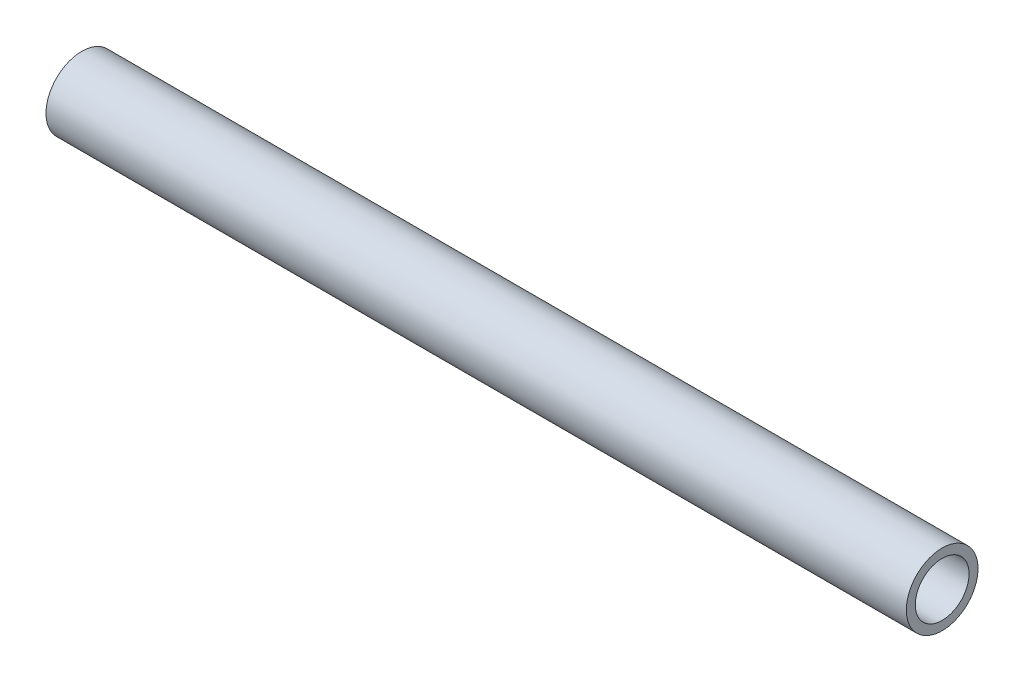
SolidWorks part; units mm, degrees
ref_plane "Front Plane" through (0, 0, 0) normal (0, 0, 1) x (1, 0, 0)
ref_plane "Top Plane" through (0, 0, 0) normal (0, 1, 0) x (1, 0, 0)
ref_plane "Right Plane" through (0, 0, 0) normal (1, 0, 0) x (0, 0, -1)
sketch "Sketch1" plane through (0, 0, 0) normal (0, 0, 1) x (1, 0, 0)
  line L0 (-50.4967, 0) -> (-145.3956, 0) construction
  line L2 (0, 4.7625) -> (-152.4, 4.7625)
  line L3 (0, 4.7625) -> (0, 6.35)
  line L4 (0, 6.35) -> (-152.4, 6.35)
  line L5 (-152.4, 4.7625) -> (-152.4, 6.35)
  dimension "D1" = 152.4
  dimension "D2" = 1.5875
  dimension "D3" = 6.35
revolve "Revolve1" add sketch "Sketch1" angle 360 about L0
equation "\"radius\"=1.36548"
